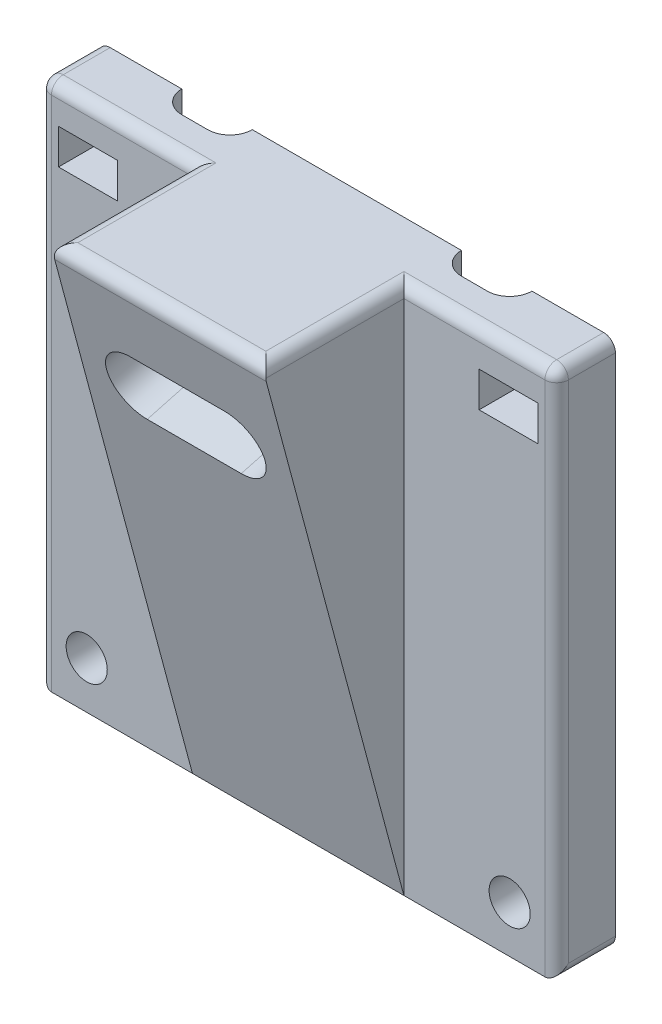
SolidWorks part; units mm, degrees
ref_plane "Front Plane" through (0, 0, 0) normal (0, 0, 1) x (1, 0, 0)
ref_plane "Top Plane" through (0, 0, 0) normal (0, 1, 0) x (1, 0, 0)
ref_plane "Right Plane" through (0, 0, 0) normal (1, 0, 0) x (0, 0, -1)
sketch "Sketch1" plane through (0, 0, 0) normal (0, 0, 1) x (1, 0, 0)
  line L1 (-22, 22.5) -> (22, 22.5)
  line L2 (-22, 22.5) -> (-22, -22.5)
  line L3 (-22, -22.5) -> (22, -22.5)
  line L4 (22, 22.5) -> (22, -22.5)
  line L5 (-22, 22.5) -> (22, -22.5) construction
  line L6 (-22, -22.5) -> (22, 22.5) construction
  point P0 (0, 0)
  dimension "D1" = 44
  dimension "D2" = 45
extrude "Base" add sketch "Sketch1" along normal blind 5
sketch "Sketch2" plane through (0, 22.5, 0) normal (0, 1, 0) x (1, 0, 0)
  line L0 (22, 0) -> (-22, 0) construction
  line L1 (-14.9, 0) -> (-8.9, 0)
  line L2 (0, 0) -> (0, -5) construction
  line L3 (22, -5) -> (-22, -5) construction
  line L5 (-14.9, 0) -> (-14.9, -5) construction
  line L6 (-13, -1.9) -> (-10.8, -1.9)
  line L7 (13, -1.9) -> (10.8, -1.9)
  line L8 (14.9, 0) -> (8.9, 0)
  arc A2 (-14.9, 0) -> (-13, -1.9) centre (-13, 0) ccw
  arc A3 (-10.8, -1.9) -> (-8.9, 0) centre (-10.8, 0) ccw
  arc A4 (14.9, 0) -> (13, -1.9) centre (13, 0) cw
  arc A5 (10.8, -1.9) -> (8.9, 0) centre (10.8, 0) cw
  point P0 (-11.9, 0)
  dimension "D1" = 11.9
  dimension "D2" = 6
  dimension "D3" = 1.9
extrude "Wire Grooves" cut sketch "Sketch2" against normal through all
sketch "Sketch4" plane through (22, 0, 0) normal (1, 0, 0) x (0, 0, -1)
  line L0 (-5, -22.5) -> (-5, 22.5)
  line L1 (-5, -22.5) -> (-17.0577, 22.5)
  line L2 (-17.0577, 22.5) -> (-5, 22.5)
  dimension "D1" = 15
extrude "Slanted Screw Platform" add sketch "Sketch4" against normal mid plane 18 from surface at -22 starting at plane "Right Plane"
sketch "Sketch5" plane through (0, -2.7572, 10.2901) normal (0, -0.2588, 0.9659) x (1, 0, 0)
  line L0 (0, 0) -> (0, 26.1482) construction
  line L1 (-9, 26.1482) -> (9, 26.1482) construction
  line L2 (-4, 16.5) -> (4, 16.5) construction
  line L3 (-4, 19.25) -> (4, 19.25)
  line L4 (-4, 13.75) -> (4, 13.75)
  arc A1 (-4, 19.25) -> (-4, 13.75) centre (-4, 16.5) ccw
  arc A2 (4, 13.75) -> (4, 19.25) centre (4, 16.5) ccw
  point P7 (0, 16.5)
  point P12 (0, 0)
  dimension "D1" = 16.5
  dimension "D2" = 2.75
  dimension "D3" = 8
extrude "Mounting Hole Screw Insertion" cut sketch "Sketch5" against normal through all
sketch "Sketch6" plane through (0, 0, 5) normal (0, 0, 1) x (1, 0, 0)
  line L0 (0, 22.5) -> (0, -22.5) construction
  line L1 (-9, 22.5) -> (9, 22.5) construction
  line L2 (-9, -22.5) -> (9, -22.5) construction
  line L3 (-22, 22.5) -> (-22, -22.5) construction
  line L4 (-20.4, 19.5) -> (-15.4, 19.5)
  line L5 (-20.4, 19.5) -> (-20.4, 16.5)
  line L6 (-20.4, 16.5) -> (-15.4, 16.5)
  line L7 (-15.4, 19.5) -> (-15.4, 16.5)
  line L8 (20.4, 16.5) -> (15.4, 16.5)
  line L9 (15.4, 19.5) -> (15.4, 16.5)
  line L10 (20.4, 19.5) -> (15.4, 19.5)
  line L11 (20.4, 19.5) -> (20.4, 16.5)
  line L12 (-9, 22.5) -> (-22, 22.5) construction
  point P10 (-17.9, 19.5)
  dimension "D1" = 5
  dimension "D2" = 3
  dimension "D3" = 3
  dimension "D4" = 4.1
extrude "Zip Tie Slots" cut sketch "Sketch6" against normal through all
sketch "Sketch7" plane through (0, 0, 5) normal (0, 0, 1) x (1, 0, 0)
  line L0 (-22, 22.5) -> (-22, -22.5) construction
  line L1 (-22, -22.5) -> (-9, -22.5) construction
  line L2 (0, 22.5) -> (0, -22.5) construction
  line L3 (-9, 22.5) -> (9, 22.5) construction
  line L4 (-9, -22.5) -> (9, -22.5) construction
  circle A0 centre (-18, -18.5) radius 1.75
  circle A1 centre (18, -18.5) radius 1.75
  dimension "D1" = 3.5
  dimension "D2" = 4
  dimension "D3" = 4
extrude "Mount Clamping Holes" cut sketch "Sketch7" against normal through all
fillet "Edge Fillets" radius 1 11 edges at (22, 0, 5) (-9, 22.5, 11.0289) (0, 22.5, 17.0577) (9, 22.5, 11.0289) (15.5, 22.5, 5) (-22, 0, 5) (-15.5, 22.5, 5) (22, -22.5, 2.5) (-22, -22.5, 2.5) (22, 22.5, 2.5) (-22, 22.5, 2.5)
